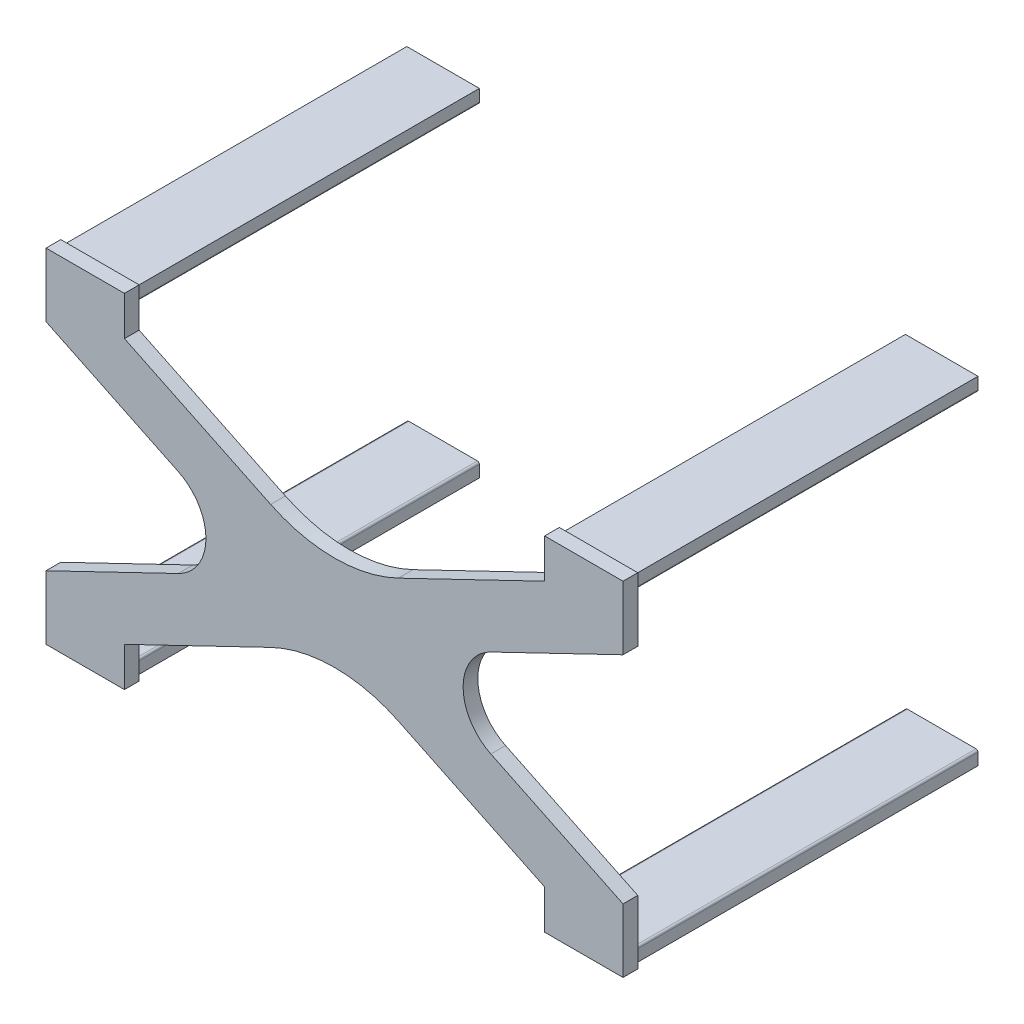
SolidWorks part; units mm, degrees
material "PETG"
ref_plane "Front Plane" through (0, 0, 0) normal (0, 0, 1) x (1, 0, 0)
ref_plane "Top Plane" through (0, 0, 0) normal (0, 1, 0) x (1, 0, 0)
ref_plane "Right Plane" through (0, 0, 0) normal (1, 0, 0) x (0, 0, -1)
sketch "Эскиз1" plane through (0, 0, 0) normal (0, 0, 1) x (1, 0, 0)
  line L0 (-50.85, 35) -> (-50.85, -35) construction
  line L1 (-85, -35) -> (85, -35)
  line L2 (-85, -35) -> (-85, 35)
  line L3 (-85, 35) -> (85, 35)
  line L4 (85, -35) -> (85, 35)
  line L5 (-85, -35) -> (85, 35) construction
  line L6 (-85, 35) -> (85, -35) construction
  line L7 (-85, 0) -> (85, 0) construction
  line L8 (-58.85, 35) -> (-58.85, 32)
  line L9 (-57.85, 31) -> (-43.85, 31)
  line L10 (-42.85, 32) -> (-42.85, 35)
  line L11 (0, 35) -> (0, -35) construction
  line L12 (-42.85, -32) -> (-42.85, -35)
  line L13 (-57.85, -31) -> (-43.85, -31)
  line L14 (-58.85, -35) -> (-58.85, -32)
  line L15 (58.85, -35) -> (58.85, -32)
  line L16 (57.85, -31) -> (43.85, -31)
  line L17 (42.85, -32) -> (42.85, -35)
  line L18 (42.85, 32) -> (42.85, 35)
  line L19 (57.85, 31) -> (43.85, 31)
  line L20 (58.85, 35) -> (58.85, 32)
  line L21 (-58.85, 32) -> (-58.85, 22)
  line L22 (-58.85, 22) -> (42.85, -27)
  line L23 (42.85, -27) -> (42.85, -32)
  line L24 (-42.85, 32) -> (-42.85, 27)
  line L25 (-42.85, 27) -> (58.85, -22)
  line L26 (58.85, -22) -> (58.85, -32)
  line L27 (42.85, 32) -> (42.85, 27)
  line L28 (42.85, 27) -> (-58.85, -22)
  line L29 (-58.85, -22) -> (-58.85, -32)
  line L30 (58.85, 32) -> (58.85, 22)
  line L31 (58.85, 22) -> (-42.85, -27)
  line L32 (-42.85, -27) -> (-42.85, -32)
  arc A0 (-43.85, 31) -> (-42.85, 32) centre (-43.85, 32) ccw
  arc A1 (-58.85, 32) -> (-57.85, 31) centre (-57.85, 32) ccw
  arc A2 (-43.85, -31) -> (-42.85, -32) centre (-43.85, -32) cw
  arc A3 (-58.85, -32) -> (-57.85, -31) centre (-57.85, -32) cw
  arc A4 (58.85, -32) -> (57.85, -31) centre (57.85, -32) ccw
  arc A5 (43.85, -31) -> (42.85, -32) centre (43.85, -32) ccw
  arc A6 (43.85, 31) -> (42.85, 32) centre (43.85, 32) cw
  arc A7 (58.85, 32) -> (57.85, 31) centre (57.85, 32) cw
  point P0 (0, 0)
  point P16 (-42.85, 31)
  point P19 (-58.85, 31)
  dimension "D7" = 1
  dimension "D1" = 170
  dimension "D2" = 70
  dimension "D3" = 34.15
  dimension "D4" = 16
  dimension "D5" = 8
  dimension "D6" = 4
  dimension "D8" = 10
  dimension "D9" = 5
extrude "Бобышка-Вытянуть1" add sketch "Эскиз1" along normal blind 3 contours A1 L21 L22 L28 L25 L24 A0 L9 | L30 A7 L19 A6 L27 L28 L25 L31 | L29 A3 L13 A2 L32 L31 L22 L28 | A5 L16 A4 L26 L25 L31 L22 L23 | L31 L25 L28 L22 | L8 A1 L9 A0 L10 L3 | A3 L14 L1 L12 A2 L13 | L16 A5 L17 L1 L15 A4 | A7 L20 L3 L18 A6 L19
fillet "Скругление1" radius 30 2 edges at (0, -6.3545, 1.5) (0, 6.3545, 1.5)
fillet "Скругление2" radius 10 2 edges at (13.1888, 0, 1.5) (-13.1888, 0, 1.5)
sketch "Эскиз2" plane through (0, 0, 0) normal (0, 0, -1) x (-1, 0, 0)
  line L0 (42.85, 32) -> (42.85, 35) construction
  line L4 (57.85, 31) -> (43.85, 31) construction
  line L5 (58.85, 35) -> (58.85, 32) construction
  line L6 (-58.85, -35) -> (-58.85, -32) construction
  line L7 (-57.85, -31) -> (-43.85, -31) construction
  line L8 (58.85, -35) -> (58.85, -32) construction
  line L12 (57.85, -31) -> (43.85, -31) construction
  line L13 (42.85, -32) -> (42.85, -35) construction
  line L20 (-58.85, 35) -> (-58.85, 32) construction
  line L21 (-57.85, 31) -> (-43.85, 31) construction
  line L22 (-42.85, 32) -> (-42.85, 35) construction
  line L23 (-42.85, -32) -> (-42.85, -35) construction
  line L24 (85, -35) -> (-85, -35) construction
  line L26 (85, 35) -> (-85, 35) construction
  line L28 (42.85, 32) -> (42.85, 35)
  line L29 (-58.25, 34.4) -> (-58.25, 32)
  line L30 (-57.85, 31.6) -> (-43.85, 31.6)
  line L31 (-43.45, 32) -> (-43.45, 34.4)
  line L32 (57.85, 31) -> (43.85, 31)
  line L33 (58.85, 35) -> (58.85, 32)
  line L34 (-58.85, -35) -> (-58.85, -32)
  line L35 (-57.85, -31) -> (-43.85, -31)
  line L36 (58.85, -35) -> (58.85, -32)
  line L37 (-43.45, 34.4) -> (-58.25, 34.4)
  line L38 (-57.85, -31.6) -> (-43.85, -31.6)
  line L39 (-43.45, -32) -> (-43.45, -34.4)
  line L40 (57.85, -31) -> (43.85, -31)
  line L41 (42.85, -32) -> (42.85, -35)
  line L42 (-43.45, -34.4) -> (-58.25, -34.4)
  line L43 (-58.25, -34.4) -> (-58.25, -32)
  line L44 (58.25, -34.4) -> (58.25, -32)
  line L45 (57.85, -31.6) -> (43.85, -31.6)
  line L46 (43.45, -32) -> (43.45, -34.4)
  line L47 (58.25, -34.4) -> (43.45, -34.4)
  line L48 (-58.85, 35) -> (-58.85, 32)
  line L49 (-57.85, 31) -> (-43.85, 31)
  line L50 (-42.85, 32) -> (-42.85, 35)
  line L51 (-42.85, -32) -> (-42.85, -35)
  line L52 (58.85, -35) -> (42.85, -35)
  line L54 (58.85, 35) -> (42.85, 35)
  line L56 (-42.85, -35) -> (-58.85, -35)
  line L57 (-42.85, 35) -> (-58.85, 35)
  line L58 (43.45, 32) -> (43.45, 34.4)
  line L59 (58.25, 34.4) -> (43.45, 34.4)
  line L60 (58.25, 34.4) -> (58.25, 32)
  line L61 (57.85, 31.6) -> (43.85, 31.6)
  line L62 (-50.85, 34.4) -> (-50.85, 31.6) construction
  arc A0 (42.85, 32) -> (43.85, 31) centre (43.85, 32) ccw construction
  arc A1 (57.85, 31) -> (58.85, 32) centre (57.85, 32) ccw construction
  arc A2 (-42.85, -32) -> (-43.85, -31) centre (-43.85, -32) ccw construction
  arc A3 (-57.85, -31) -> (-58.85, -32) centre (-57.85, -32) ccw construction
  arc A4 (43.85, -31) -> (42.85, -32) centre (43.85, -32) ccw construction
  arc A5 (58.85, -32) -> (57.85, -31) centre (57.85, -32) ccw construction
  arc A6 (-43.85, 31) -> (-42.85, 32) centre (-43.85, 32) ccw construction
  arc A7 (-58.85, 32) -> (-57.85, 31) centre (-57.85, 32) ccw construction
  arc A8 (42.85, 32) -> (43.85, 31) centre (43.85, 32) ccw
  arc A9 (57.85, 31) -> (58.85, 32) centre (57.85, 32) ccw
  arc A10 (-42.85, -32) -> (-43.85, -31) centre (-43.85, -32) ccw
  arc A11 (-57.85, -31) -> (-58.85, -32) centre (-57.85, -32) ccw
  arc A12 (43.85, -31) -> (42.85, -32) centre (43.85, -32) ccw
  arc A13 (58.85, -32) -> (57.85, -31) centre (57.85, -32) ccw
  arc A14 (-43.85, 31) -> (-42.85, 32) centre (-43.85, 32) ccw
  arc A15 (-58.85, 32) -> (-57.85, 31) centre (-57.85, 32) ccw
  arc A16 (-58.25, 32) -> (-57.85, 31.6) centre (-57.85, 32) ccw
  arc A17 (-43.85, 31.6) -> (-43.45, 32) centre (-43.85, 32) ccw
  arc A18 (-43.45, -32) -> (-43.85, -31.6) centre (-43.85, -32) ccw
  arc A19 (-57.85, -31.6) -> (-58.25, -32) centre (-57.85, -32) ccw
  arc A20 (58.25, -32) -> (57.85, -31.6) centre (57.85, -32) ccw
  arc A21 (43.85, -31.6) -> (43.45, -32) centre (43.85, -32) ccw
  arc A22 (57.85, 31.6) -> (58.25, 32) centre (57.85, 32) ccw
  arc A23 (43.45, 32) -> (43.85, 31.6) centre (43.85, 32) ccw
  dimension "D1" = 0.6
  dimension "D2" = 0.6
  dimension "D3" = 0.6
  dimension "D4" = 0.6
extrude "Бобышка-Вытянуть2" add sketch "Эскиз2" along normal blind 70 separate body contours L62 L37 L29 A16 L30 | L37 L62 L30 A17 L31 | L38 A19 L43 L42 L39 A18 | L45 A21 L46 L47 L44 A20 | L58 A23 L61 A22 L60 L59
